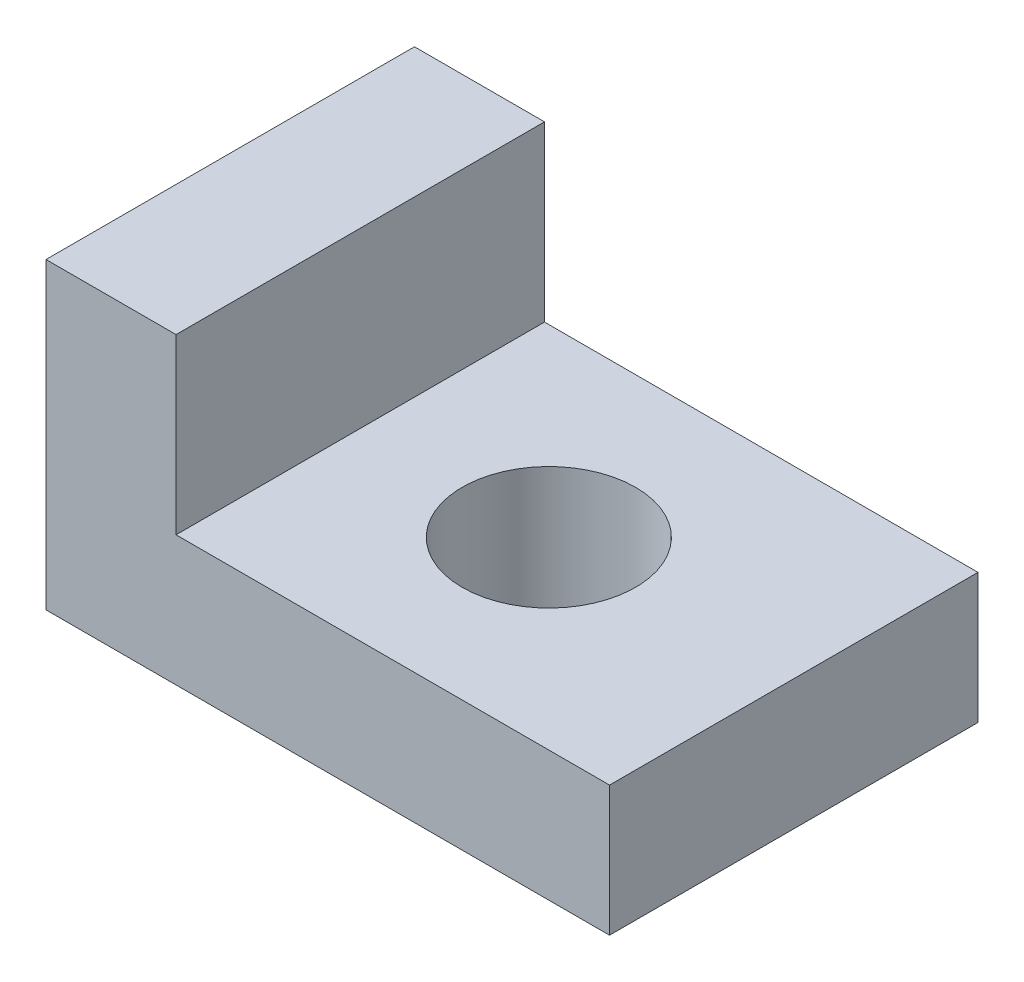
SolidWorks part; units mm, degrees
ref_plane "Front Plane" through (0, 0, 0) normal (0, 0, 1) x (1, 0, 0)
ref_plane "Top Plane" through (0, 0, 0) normal (0, 1, 0) x (1, 0, 0)
ref_plane "Right Plane" through (0, 0, 0) normal (1, 0, 0) x (0, 0, -1)
sketch "Sketch1" plane through (0, 0, 0) normal (0, 1, 0) x (1, 0, 0)
  line L1 (-6.5, 4.25) -> (6.5, 4.25)
  line L2 (-6.5, 4.25) -> (-6.5, -4.25)
  line L3 (-6.5, -4.25) -> (6.5, -4.25)
  line L4 (6.5, 4.25) -> (6.5, -4.25)
  line L5 (-6.5, 4.25) -> (6.5, -4.25) construction
  line L6 (-6.5, -4.25) -> (6.5, 4.25) construction
  point P0 (0, 0)
  dimension "D1" = 13
  dimension "D2" = 8.5
extrude "Boss-Extrude2" add sketch "Sketch1" along normal blind 3 contours L2 L1 L4 L3
sketch "Sketch2" plane through (0, 0, 0) normal (0, 1, 0) x (1, 0, 0)
  line L0 (-6.5, 4.25) -> (-6.5, -4.25) construction
  circle A0 centre (0.85, 0) radius 2
  dimension "D1" = 7.35
extrude "Cut-Extrude1" cut sketch "Sketch2" along normal through all
sketch "Sketch3" plane through (0, 3, 0) normal (0, 1, 0) x (1, 0, 0)
  line L0 (-6.5, -4.25) -> (6.5, -4.25) construction
  line L1 (-6.5, 4.25) -> (-3.5, 4.25)
  line L2 (-6.5, 4.25) -> (-6.5, -4.25)
  line L3 (-6.5, -4.25) -> (-3.5, -4.25)
  line L4 (-3.5, 4.25) -> (-3.5, -4.25)
  dimension "D1" = 3
extrude "Boss-Extrude3" add sketch "Sketch3" along normal blind 4
